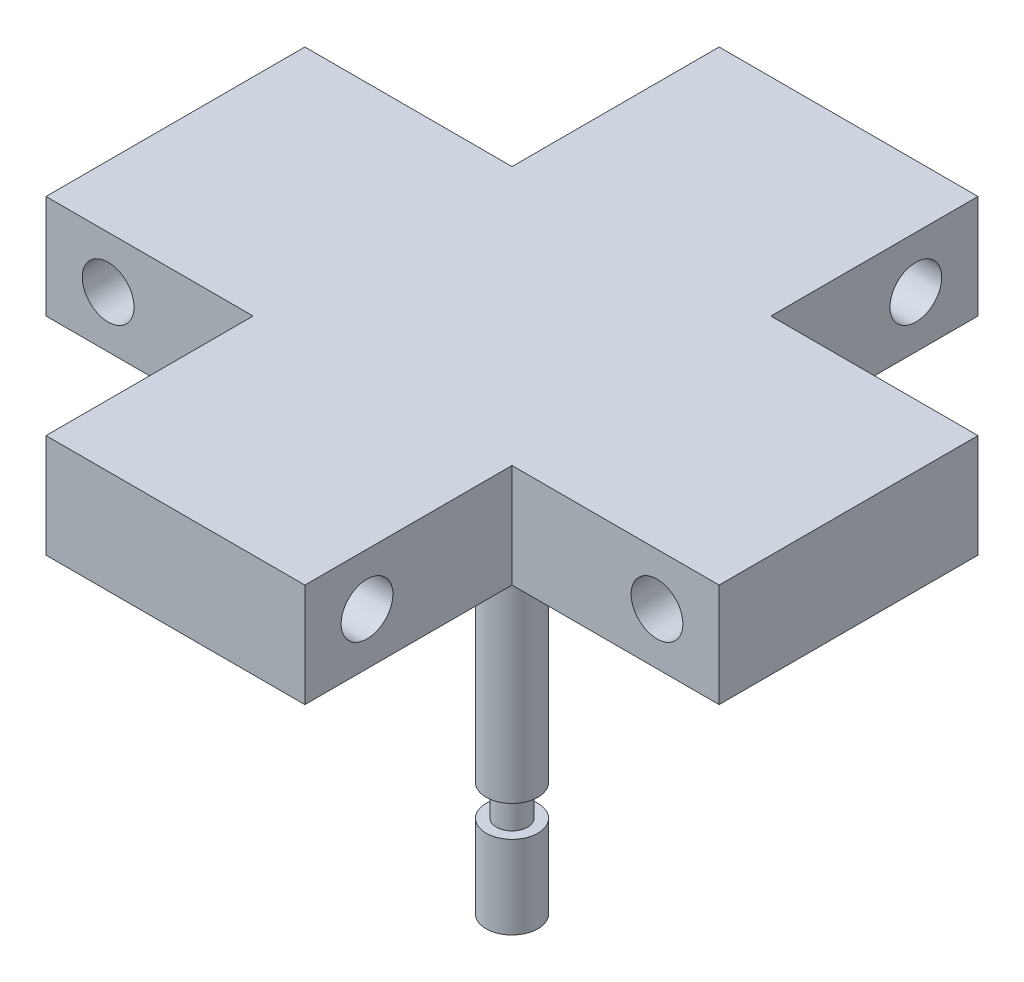
SolidWorks part; units mm, degrees
ref_plane "Front Plane" through (0, 0, 0) normal (0, 0, 1) x (1, 0, 0)
ref_plane "Top Plane" through (0, 0, 0) normal (0, 1, 0) x (1, 0, 0)
ref_plane "Right Plane" through (0, 0, 0) normal (1, 0, 0) x (0, 0, -1)
sketch "Sketch1" plane through (0, 0, 0) normal (0, 1, 0) x (1, 0, 0)
  line L1 (12.5, -12.5) -> (-12.5, -12.5)
  line L2 (12.5, -12.5) -> (12.5, 12.5)
  line L3 (12.5, 12.5) -> (-12.5, 12.5)
  line L4 (-12.5, -12.5) -> (-12.5, 12.5)
  line L5 (12.5, -12.5) -> (-12.5, 12.5) construction
  line L6 (12.5, 12.5) -> (-12.5, -12.5) construction
  line L7 (-12.5, 12.5) -> (12.5, 12.5)
  line L8 (-12.5, 12.5) -> (-12.5, 32.5)
  line L9 (-12.5, 32.5) -> (12.5, 32.5)
  line L10 (12.5, 12.5) -> (12.5, 32.5)
  line L11 (12.5, 12.5) -> (32.5, 12.5)
  line L12 (12.5, 12.5) -> (12.5, -12.5)
  line L13 (12.5, -12.5) -> (32.5, -12.5)
  line L14 (32.5, 12.5) -> (32.5, -12.5)
  line L15 (12.5, -12.5) -> (-12.5, -12.5)
  line L16 (12.5, -12.5) -> (12.5, -32.5)
  line L17 (12.5, -32.5) -> (-12.5, -32.5)
  line L18 (-12.5, -12.5) -> (-12.5, -32.5)
  line L19 (-12.5, 12.5) -> (-32.5, 12.5)
  line L20 (-12.5, 12.5) -> (-12.5, -12.5)
  line L21 (-12.5, -12.5) -> (-32.5, -12.5)
  line L22 (-32.5, 12.5) -> (-32.5, -12.5)
  point P0 (0, 0)
  dimension "D1" = 25
  dimension "D2" = 65
  dimension "D3" = 65
extrude "Boss-Extrude1" add sketch "Sketch1" along normal blind 10 contours L19 L22 L21 L4 | L1 L18 L17 L16 | L4 L1 L2 L3 | L3 L10 L9 L8 | L14 L11 L2 L13
sketch "Sketch2" plane through (12.5, 0, 0) normal (1, 0, 0) x (0, 0, -1)
  circle A0 centre (-26.5, 5) radius 2.5
  circle A1 centre (26.5, 5) radius 2.5
extrude "Cut-Extrude1" cut sketch "Sketch2" against normal through all
sketch "Sketch3" plane through (0, 0, 12.5) normal (0, 0, 1) x (1, 0, 0)
  circle A0 centre (26.5, 5) radius 2.5 construction
  circle A1 centre (-26.5, 5) radius 2.5 construction
  circle A2 centre (26.5, 5) radius 2.5
  circle A3 centre (-26.5, 5) radius 2.5
extrude "Cut-Extrude2" cut sketch "Sketch3" against normal through all
sketch "Sketch4" plane through (0, 0, 0) normal (0, 1, 0) x (1, 0, 0)
  circle A0 centre (0, 0) radius 2.5
  dimension "D1" = 5
extrude "Boss-Extrude2" add sketch "Sketch4" against normal blind 40
sketch "Sketch5" plane through (0, 0, 0) normal (1, 0, 0) x (0, 0, -1)
  line L0 (0, 0) -> (0, -40) construction
  line L1 (-2.5, -40) -> (2.5, -40) construction
  line L2 (2.5, -29) -> (1.5, -29)
  line L4 (2.5, -40) -> (2.5, 0) construction
  line L5 (1.5, -29) -> (1.5, -32)
  line L6 (1.5, -32) -> (2.5, -32)
  line L7 (2.5, -29) -> (2.5, -32)
  dimension "D1" = 1
  dimension "D2" = 8
  dimension "D3" = 3
revolve "Cut-Revolve1" cut sketch "Sketch5" angle 360 about L0
